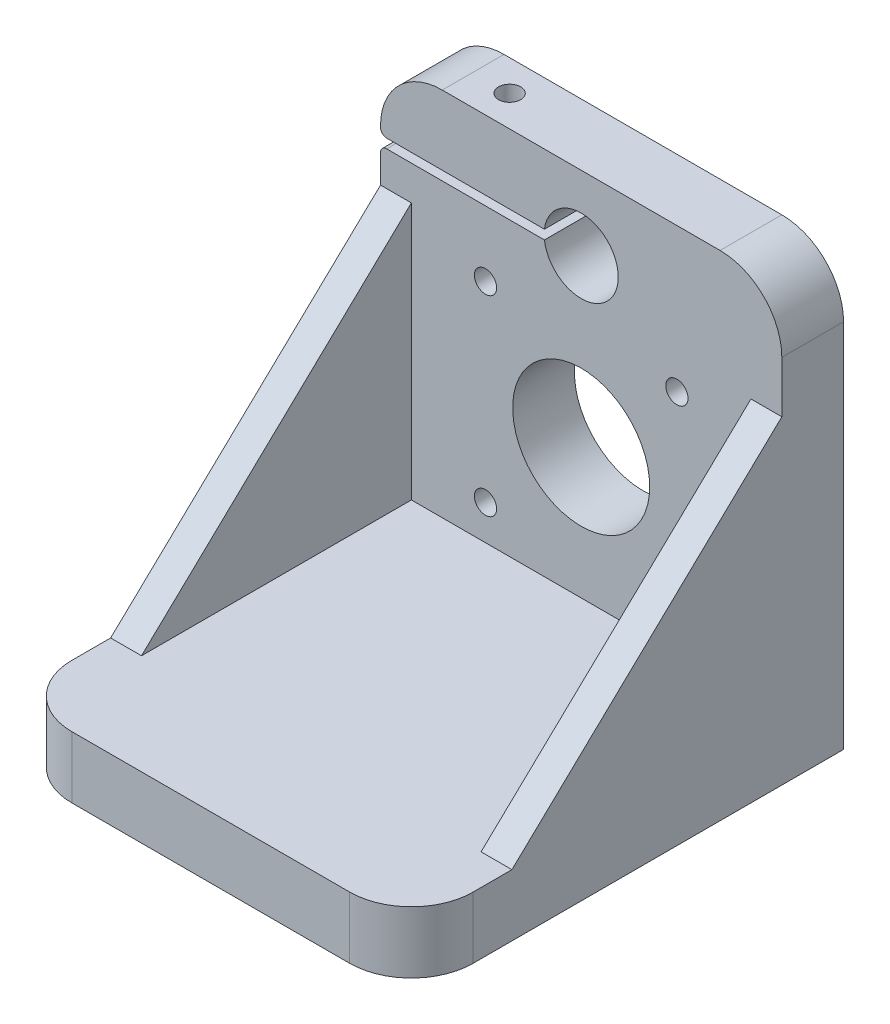
SolidWorks part; units mm, degrees
ref_plane "Front Plane" through (0, 0, 0) normal (0, 0, 1) x (1, 0, 0)
ref_plane "Top Plane" through (0, 0, 0) normal (0, 1, 0) x (1, 0, 0)
ref_plane "Right Plane" through (0, 0, 0) normal (1, 0, 0) x (0, 0, -1)
sketch "Sketch1" plane through (0, 0, 0) normal (0, 1, 0) x (1, 0, 0)
  line L1 (-32.5, 35) -> (32.5, 35)
  line L2 (-32.5, 35) -> (-32.5, -35)
  line L3 (-32.5, -35) -> (32.5, -35)
  line L4 (32.5, 35) -> (32.5, -35)
  line L5 (-32.5, 35) -> (32.5, -35) construction
  line L6 (-32.5, -35) -> (32.5, 35) construction
  point P0 (0, 0)
  dimension "D1" = 70
  dimension "D2" = 65
extrude "Boss-Extrude1" add sketch "Sketch1" along normal blind 10 contours L2 L1 L4 L3
sketch "Sketch2" plane through (0, 10, 0) normal (0, 1, 0) x (1, 0, 0)
  line L0 (-32.5, 35) -> (-32.5, -35) construction
  line L1 (-32.5, 35) -> (32.5, 35)
  line L2 (-32.5, 35) -> (-32.5, 25)
  line L3 (-32.5, 25) -> (32.5, 25)
  line L4 (32.5, 35) -> (32.5, 25)
  line L5 (-32.5, 35) -> (32.5, 35) construction
  line L6 (32.5, 35) -> (32.5, -35) construction
  dimension "D1" = 10
extrude "Boss-Extrude2" add sketch "Sketch2" along normal blind 60
fillet "Fillet1" radius 10 2 edges at (32.5, 5, 35) (-32.5, 5, 35)
sketch "Sketch3" plane through (0, 0, -25) normal (0, 0, 1) x (1, 0, 0)
  line L1 (-32.5, 70) -> (-32.5, 10) construction
  line L7 (-5.9529, 58.75) -> (-32.5, 58.75)
  line L9 (-5.9529, 57.25) -> (-32.5, 57.25)
  line L10 (-32.5, 58.75) -> (-32.5, 57.25)
  arc A0 (-5.9529, 57.25) -> (-5.9529, 58.75) centre (0, 58) ccw
  point P11 (-16.2737, 58)
  dimension "D3" = 1.5
extrude "Cut-Extrude3" cut sketch "Sketch3" against normal blind 60
fillet "Fillet2" radius 10 2 edges at (-32.5, 70, -30) (32.5, 70, -30)
fillet "Fillet3" radius 1 1 edges at (-32.5, 58.75, -30)
fillet "Fillet4" radius 1 1 edges at (-32.5, 57.25, -30)
sketch "Sketch4" plane through (0, 0, -25) normal (0, 0, 1) x (1, 0, 0)
  line L0 (-32.5, 10) -> (32.5, 10) construction
  line L1 (0, 10) -> (0, 31.15) construction
  circle A0 centre (0, 31.15) radius 11.1
  dimension "D1" = 21.15
extrude "Cut-Extrude4" cut sketch "Sketch4" against normal blind 60
sketch "Sketch5" plane through (-32.5, 0, 0) normal (-1, 0, 0) x (0, 0, 1)
  line L0 (-25, 51.6659) -> (18.7176, 10)
  line L1 (-25, 56.25) -> (-25, 10) construction
  line L2 (-25, 10) -> (25, 10) construction
rib "Rib1" sketch "Sketch5" sketch "Sketch5" thickness 5 extrusion direction parallel to sketch draft on no parameters "D1"=5
mirror "Mirror1" about plane through (0, 0, 0) normal (1, 0, 0) of "Rib1"
sketch "Sketch6" plane through (0, 70, 0) normal (0, 1, 0) x (1, 0, 0)
  line L0 (22.5, 35) -> (-22.5, 35) construction
  circle A0 centre (-16.5973, 30) radius 1.8
  point P2 (-16.4327, 29.7759)
  point P3 (-18.3751, 29.4493)
  point P4 (-16.5973, 29.5285)
  dimension "D1" = 5
extrude "Cut-Extrude5" cut sketch "Sketch6" against normal blind 20
sketch "Sketch7" plane through (0, 0, -25) normal (0, 0, 1) x (1, 0, 0)
  circle A0 centre (-15.5, 46.65) radius 1.8
  circle A1 centre (15.5, 46.65) radius 1.8
  circle A2 centre (15.5, 15.65) radius 1.8
  circle A3 centre (-15.5, 15.65) radius 1.8
  point P0 (0, 31.15)
  point P7 (0, 0)
  point P10 (0, 0)
  point P11 (15.5, 46.6051)
  point P13 (0, 0)
  point P14 (15.5, 15.7282)
  point P16 (-15.7007, 15.65)
extrude "Cut-Extrude8" cut sketch "Sketch7" against normal blind 10 contours A0 | A1 | A3 | A2
sketch "Sketch9" plane through (0, 0, -35) normal (0, 0, -1) x (-1, 0, 0)
  circle A0 centre (-15.5, 46.65) radius 3
  circle A1 centre (15.5, 46.65) radius 3
  circle A2 centre (15.5, 15.65) radius 3
  circle A3 centre (-15.5, 15.65) radius 3
  point P0 (0, 31.15)
  point P8 (0, 0)
  point P11 (0, 0)
  point P12 (15.4828, 46.65)
  point P14 (0, 0)
  point P15 (15.5, 15.6792)
  point P17 (0, 0)
  point P18 (-15.5, 15.5783)
extrude "Cut-Extrude9" cut sketch "Sketch9" against normal blind 5 contours A0 | A1 | A2 | A3
